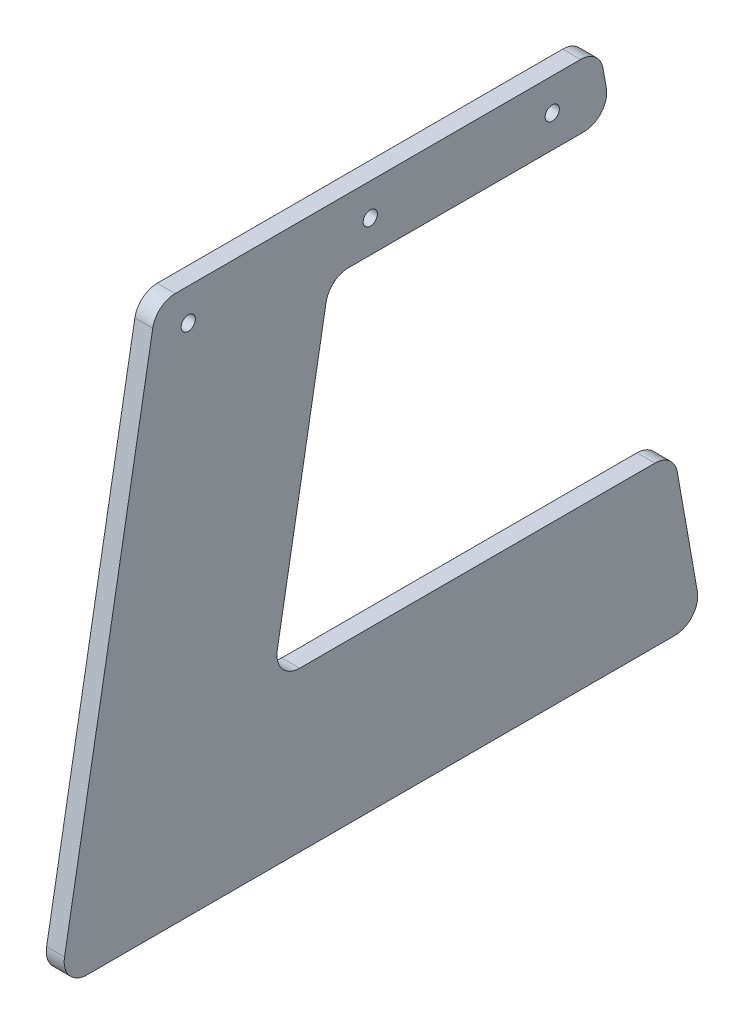
SolidWorks part; units mm, degrees
ref_plane "Front Plane" through (0, 0, 0) normal (0, 0, 1) x (1, 0, 0)
ref_plane "Top Plane" through (0, 0, 0) normal (0, 1, 0) x (1, 0, 0)
ref_plane "Right Plane" through (0, 0, 0) normal (1, 0, 0) x (0, 0, -1)
sketch "Sketch1" plane through (0, 0, 0) normal (1, 0, 0) x (0, 0, -1)
  line L0 (98.9556, 131.3843) -> (97.1005, 141.9053)
  line L1 (-141.7434, 152.4) -> (84.5934, 152.4)
  line L2 (-84.7686, -48.5947) -> (-57.5121, 105.9843)
  line L3 (-191.0092, -152.4) -> (137.2647, -152.4)
  line L4 (149.7718, -137.4947) -> (138.575, -73.9947)
  line L7 (86.4486, 116.479) -> (-45.005, 116.479)
  line L8 (126.068, -63.5) -> (-72.2615, -63.5)
  line L9 (-203.5163, -137.4947) -> (-154.2505, 141.9053)
  arc A0 (-141.7434, 152.4) -> (-154.2505, 141.9053) centre (-141.7434, 139.7) ccw
  circle A1 centre (-134.4395, 134.4395) radius 3.9687
  circle A2 centre (-32.8395, 134.4395) radius 3.9688
  circle A3 centre (68.7605, 134.4395) radius 3.9687
  arc A4 (84.5934, 152.4) -> (97.1005, 141.9053) centre (84.5934, 139.7) cw
  arc A5 (86.4486, 116.479) -> (98.9556, 131.3843) centre (86.4486, 129.179) ccw
  arc A6 (-72.2615, -63.5) -> (-84.7686, -48.5947) centre (-72.2615, -50.8) cw
  arc A7 (-45.005, 116.479) -> (-57.5121, 105.9843) centre (-45.005, 103.779) ccw
  arc A8 (138.575, -73.9947) -> (126.068, -63.5) centre (126.068, -76.2) ccw
  arc A9 (-203.5163, -137.4947) -> (-191.0092, -152.4) centre (-191.0092, -139.7) ccw
  arc A10 (137.2647, -152.4) -> (149.7718, -137.4947) centre (137.2647, -139.7) ccw
  point P24 (101.6, 152.4)
  point P29 (-96.4264, -114.7094)
  point P32 (136.9627, -64.8506)
  dimension "D3" = 12.7
  dimension "D4" = 3
  dimension "D5" = 12.7
  dimension "D6" = 12.7
  dimension "D7" = 12.7
  dimension "D8" = 12.7
  dimension "D1" = 12.7
  dimension "D2" = 12.7
  dimension "D9" = 12.7
  dimension "D10" = 7.9375
  dimension "D11" = 101.6
extrude "Boss-Extrude1" add sketch "Sketch1" along normal blind 10
